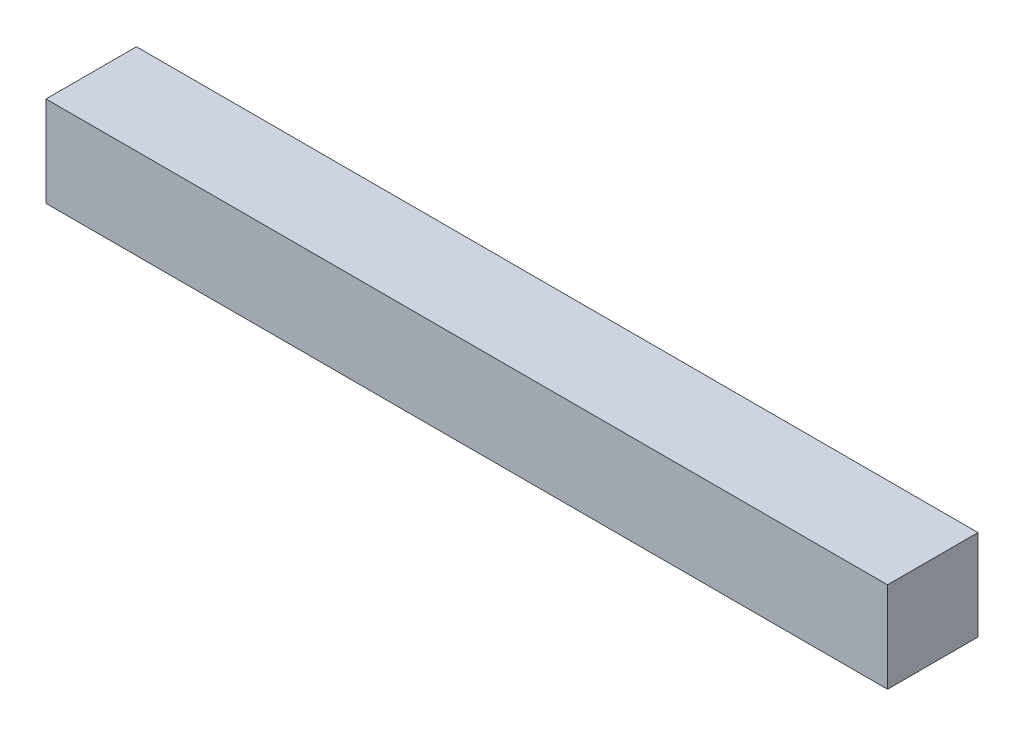
SolidWorks part; units mm, degrees
ref_plane "前视" through (0, 0, 0) normal (0, 0, 1) x (1, 0, 0)
ref_plane "上视" through (0, 0, 0) normal (0, 1, 0) x (1, 0, 0)
ref_plane "右视" through (0, 0, 0) normal (1, 0, 0) x (0, 0, -1)
sketch "草图1" plane through (0, 0, 0) normal (0, 0, 1) x (1, 0, 0)
  line L1 (0, 215) -> (2000, 215)
  line L2 (0, 215) -> (0, 0)
  line L3 (0, 0) -> (2000, 0)
  line L4 (2000, 215) -> (2000, 0)
  dimension "D1" = 2000
  dimension "D2" = 215
extrude "基体-拉伸" add sketch "草图1" along normal blind 215
